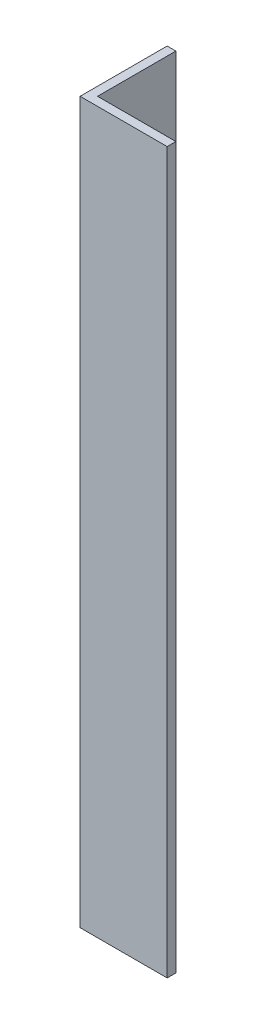
SolidWorks part; units mm, degrees
ref_plane "Front Plane" through (0, 0, 0) normal (0, 0, 1) x (1, 0, 0)
ref_plane "Top Plane" through (0, 0, 0) normal (0, 1, 0) x (1, 0, 0)
ref_plane "Right Plane" through (0, 0, 0) normal (1, 0, 0) x (0, 0, -1)
sketch "Sketch1" plane through (0, 0, 0) normal (0, 1, 0) x (1, 0, 0)
  line L0 (-12, 12) -> (-12, 15)
  line L1 (-12, -12) -> (12, -12)
  line L2 (-12, -12) -> (-12, 12)
  line L3 (-12, 12) -> (12, 12)
  line L4 (12, -12) -> (12, 12)
  line L5 (-12, -12) -> (12, 12) construction
  line L6 (-12, 12) -> (12, -12) construction
  line L7 (-15, -15) -> (15, -15)
  line L8 (-15, -15) -> (-15, 15)
  line L9 (-15, 15) -> (15, 15)
  line L10 (15, -15) -> (15, 15)
  line L11 (-15, -15) -> (15, 15) construction
  line L12 (-15, 15) -> (15, -15) construction
  line L13 (12, -12) -> (15, -12)
  point P0 (0, 0)
  point P6 (0, 0)
  dimension "D1" = 30
  dimension "D2" = 3
extrude "Boss-Extrude1" add sketch "Sketch1" along normal blind 248 contours L13 L1 L2 L0 L9 L8 L7 L10
